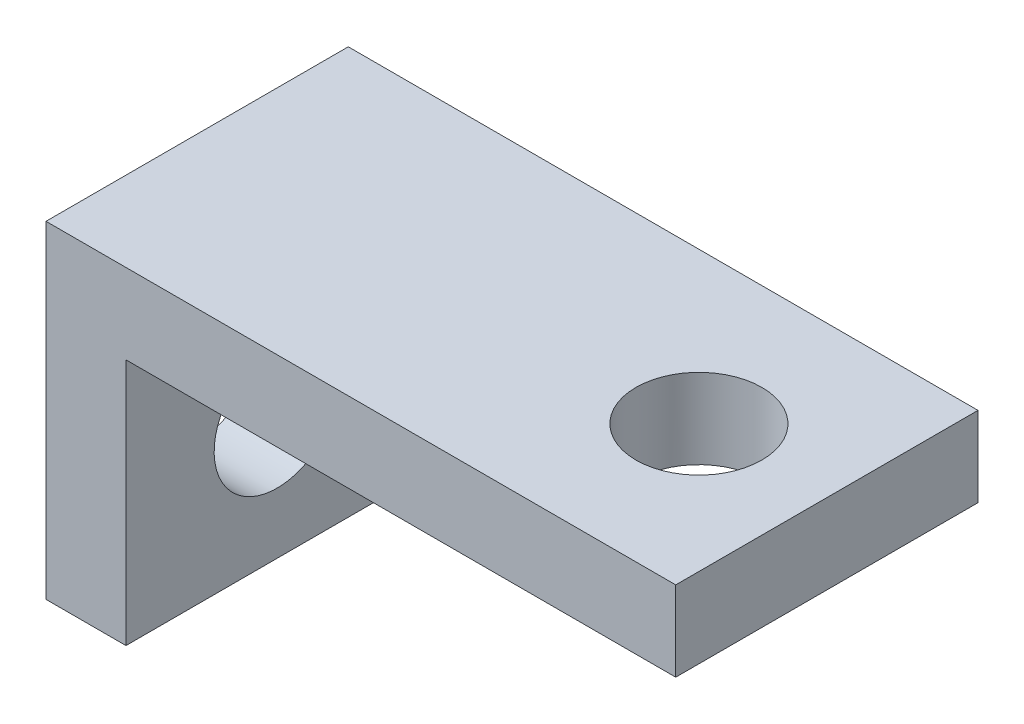
SolidWorks part; units mm, degrees
ref_plane "Front Plane" through (0, 0, 0) normal (0, 0, 1) x (1, 0, 0)
ref_plane "Top Plane" through (0, 0, 0) normal (0, 1, 0) x (1, 0, 0)
ref_plane "Right Plane" through (0, 0, 0) normal (1, 0, 0) x (0, 0, -1)
sketch "Sketch1" plane through (0, 0, 0) normal (0, 0, 1) x (1, 0, 0)
  line L1 (-0.381, -3.9917) -> (1.2065, -3.9917)
  line L2 (-0.381, -3.9917) -> (-0.381, 2.5083)
  line L3 (-0.381, 2.5083) -> (1.2065, 2.5083)
  line L4 (1.2065, -3.9917) -> (1.2065, 2.5083)
  line L5 (1.2065, 2.5083) -> (12.119, 2.5083)
  line L6 (1.2065, 2.5083) -> (1.2065, 0.9208)
  line L7 (1.2065, 0.9208) -> (12.119, 0.9208)
  line L8 (12.119, 2.5083) -> (12.119, 0.9208)
  dimension "D1" = 1.5875
  dimension "D2" = 1.5875
  dimension "D3" = 12.5
  dimension "D4" = 6.5
extrude "Boss-Extrude1" add sketch "Sketch1" along normal blind 6 contours L1 L4 L3 L2 | L8 L5 L4 L7
sketch "Sketch2" plane through (1.2065, 0, 0) normal (1, 0, 0) x (0, 0, -1)
  circle A0 centre (-3, -1.5355) radius 1.25
  dimension "D1" = 2.5
extrude "Cut-Extrude1" cut sketch "Sketch2" against normal blind 6
sketch "Sketch3" plane through (0, 0.9208, 0) normal (0, -1, 0) x (1, 0, 0)
  line L0 (12.119, 6) -> (12.119, 0) construction
  circle A0 centre (9.579, 3) radius 1.25
  dimension "D1" = 2.5
  dimension "D2" = 2.54
extrude "Cut-Extrude2" cut sketch "Sketch3" against normal blind 6
equation "\"8mmm\"=1"
